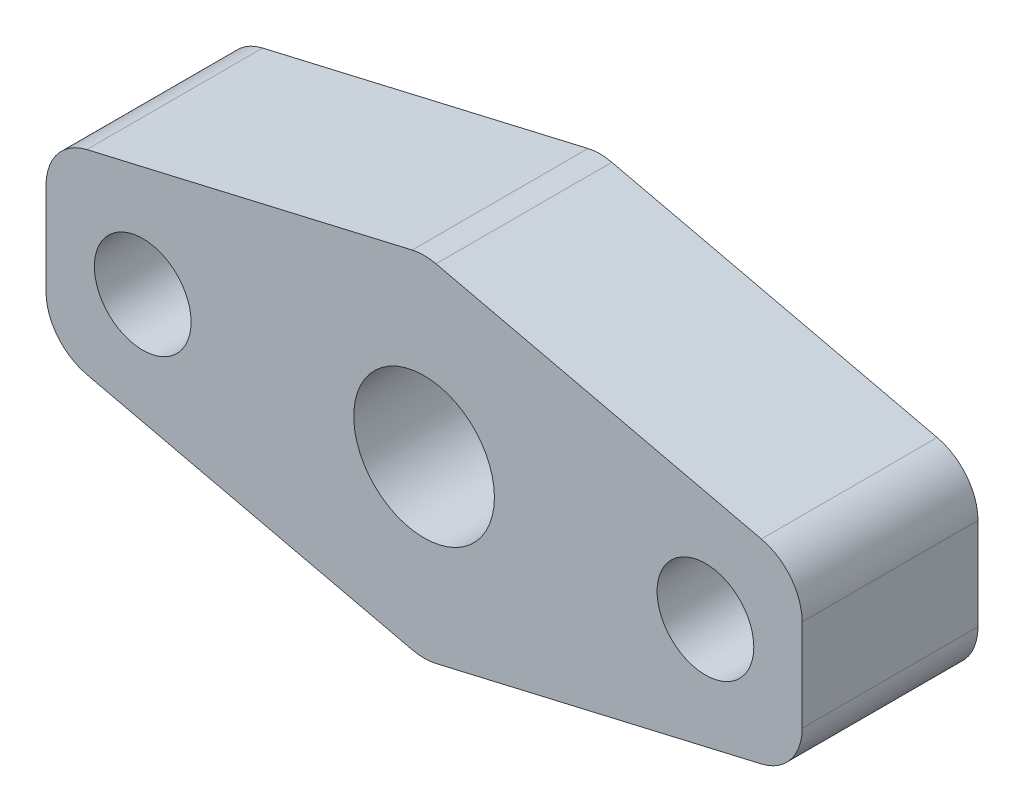
SolidWorks part; units mm, degrees
ref_plane "Front Plane" through (0, 0, 0) normal (0, 0, 1) x (1, 0, 0)
ref_plane "Top Plane" through (0, 0, 0) normal (0, 1, 0) x (1, 0, 0)
ref_plane "Right Plane" through (0, 0, 0) normal (1, 0, 0) x (0, 0, -1)
sketch "Sketch1" plane through (0, 0, 0) normal (0, 0, 1) x (1, 0, 0)
  line L0 (-712.1412, 0) -> (34894.9193, 0) construction
  line L1 (0, -712.1412) -> (0, 34894.9193) construction
  line L3 (-21.5, -5) -> (-21.5, 5)
  line L5 (21.5, -5) -> (21.5, 5)
  line L6 (-21.5, -5) -> (21.5, 5) construction
  line L7 (-21.5, 5) -> (21.5, -5) construction
  line L8 (0, 10) -> (-21.5, 5)
  line L9 (0, 10) -> (21.5, 5)
  line L10 (21.5, -5) -> (0, -10)
  line L11 (0, -10) -> (-21.5, -5)
  circle A0 centre (0, 0) radius 4
  circle A1 centre (-16, 0) radius 2.75
  circle A2 centre (16, 0) radius 2.75
  point P1 (0, 0)
  dimension "D1" = 8
  dimension "D4" = 5.5
  dimension "D2" = 20
  dimension "D3" = 43
  dimension "D5" = 16
  dimension "D6" = 16
  dimension "D7" = 10
extrude "Boss-Extrude1" add sketch "Sketch1" along normal blind 10
fillet "Fillet1" radius 3 6 edges at (0, -10, 5) (-21.5, -5, 5) (-21.5, 5, 5) (21.5, -5, 5) (21.5, 5, 5) (0, 10, 5)
sketch "Sketch2" plane through (0, 0, 0) normal (0, 0, -1) x (-1, 0, 0)
  point P0 (0, 0)
